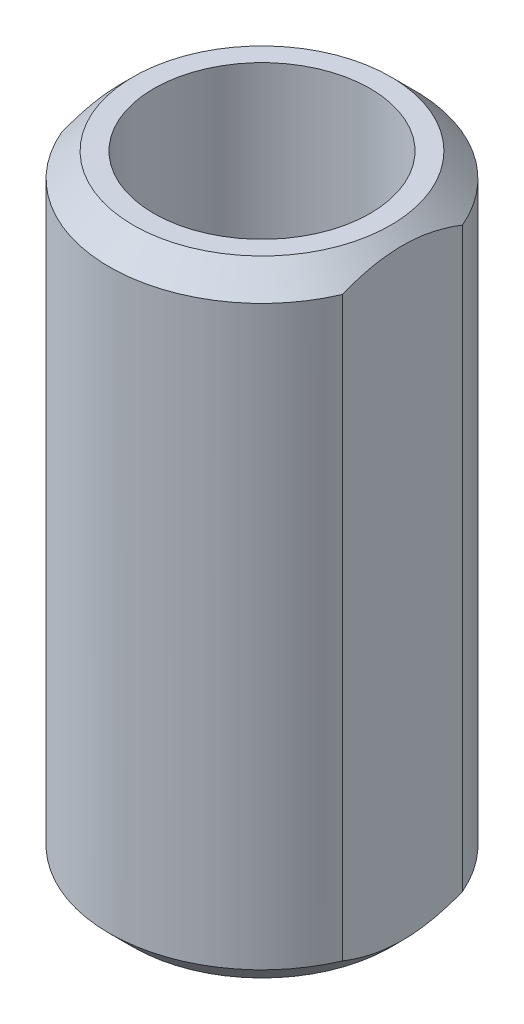
SolidWorks part; units mm, degrees
ref_plane "Front Plane" through (0, 0, 0) normal (0, 0, 1) x (1, 0, 0)
ref_plane "Top Plane" through (0, 0, 0) normal (0, 1, 0) x (1, 0, 0)
ref_plane "Right Plane" through (0, 0, 0) normal (1, 0, 0) x (0, 0, -1)
sketch "Sketch1" plane through (0, 0, 0) normal (0, 0, 1) x (1, 0, 0)
  line L0 (0, 18.0166) -> (0, -20.3529) construction
  line L1 (-4.5, 13) -> (-5.35, 13)
  line L2 (-6.35, 12) -> (-6.35, -12)
  line L3 (-5.35, -13) -> (-4.5, -13)
  line L4 (-4.5, -13) -> (-4.5, 13)
  line L5 (-5.35, 13) -> (-6.35, 12)
  line L6 (-6.35, -12) -> (-5.35, -13)
  point P4 (-6.35, 13)
  point P5 (-6.3, 0)
  point P6 (-6.35, -13)
  dimension "D1" = 9
  dimension "D2" = 12.7
  dimension "D3" = 26
revolve "Revolve1" add sketch "Sketch1" angle 360 about L0
sketch "Sketch2" plane through (0, 0, 0) normal (0, 1, 0) x (1, 0, 0)
  line L0 (-5.8372, 2.5) -> (-5.8372, -2.5)
  line L1 (5.8372, 2.5) -> (5.8372, -2.5)
  line L3 (-5.8372, 2.5) -> (-12.0381, 2.5)
  line L4 (-5.8372, -2.5) -> (-12.0381, -2.5)
  line L5 (-12.0381, 2.5) -> (-12.0381, -2.5)
  line L7 (5.8372, 2.5) -> (13.6446, 2.5)
  line L8 (5.8372, -2.5) -> (13.6446, -2.5)
  line L9 (13.6446, 2.5) -> (13.6446, -2.5)
  circle A1 centre (0, 0) radius 6.35 construction
  dimension "D1" = 5
extrude "Cut-Extrude1" cut sketch "Sketch2" against normal through all both and the other way through all
